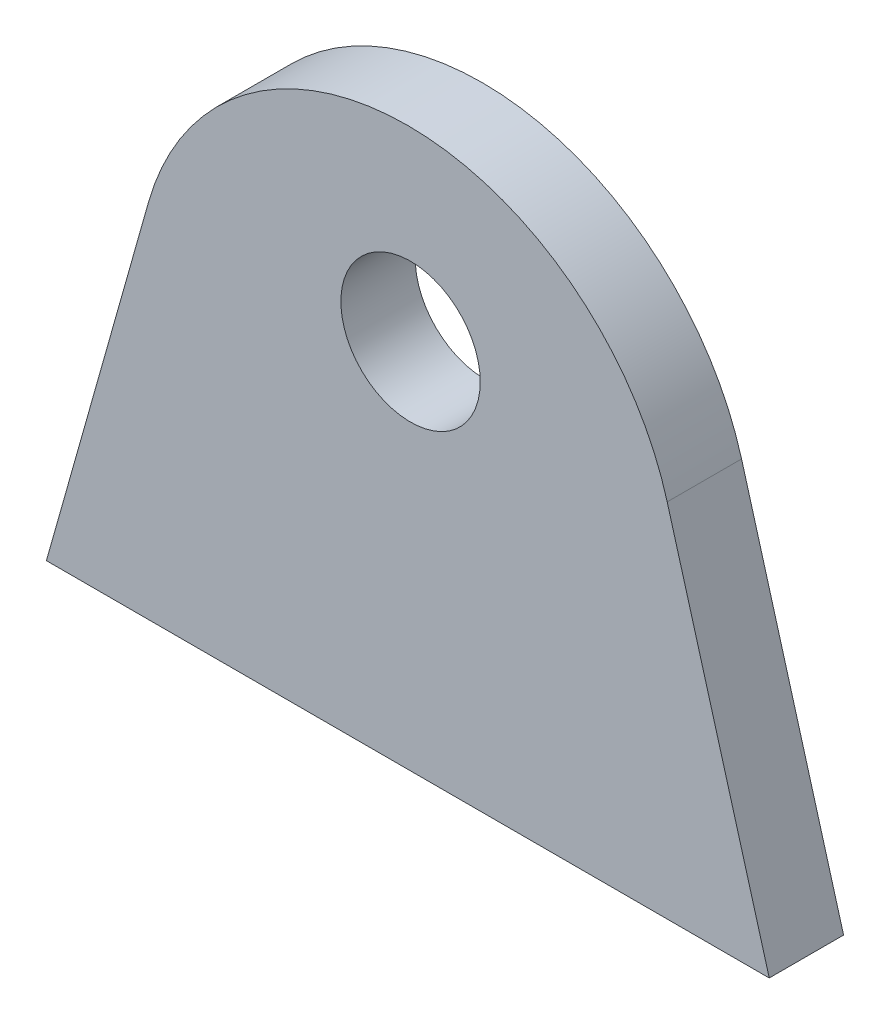
SolidWorks part; units mm, degrees
ref_plane "Front Plane" through (0, 0, 0) normal (0, 0, 1) x (1, 0, 0)
ref_plane "Top Plane" through (0, 0, 0) normal (0, 1, 0) x (1, 0, 0)
ref_plane "Right Plane" through (0, 0, 0) normal (1, 0, 0) x (0, 0, -1)
sketch "Sketch1" plane through (0, 0, 0) normal (0, 0, 1) x (1, 0, 0)
  line L3 (0, 0) -> (24.6951, 0)
  line L4 (24.6951, 0) -> (21.209, 12.3445)
  line L5 (0, 0) -> (3.4861, 12.3445)
  arc A2 (3.4861, 12.3445) -> (21.209, 12.3445) centre (12.3475, 9.842) cw
  circle A3 centre (12.4407, 12.6997) radius 2.3813
  point P7 (12.3475, 0)
  point P8 (0, 0)
  point P9 (0, 0)
  point P12 (1.115, 12.4181)
  point P13 (23.5226, 12.7324)
  point P14 (12.3475, 19.05)
  point P15 (21.1368, 12.6997)
  point P16 (0, 0)
  point P17 (0, 0)
  dimension "D4" = 4.7625
  dimension "D1" = 19.05
  dimension "D3" = 12.7
extrude "Boss-Extrude1" add sketch "Sketch1" along normal blind 2.54
